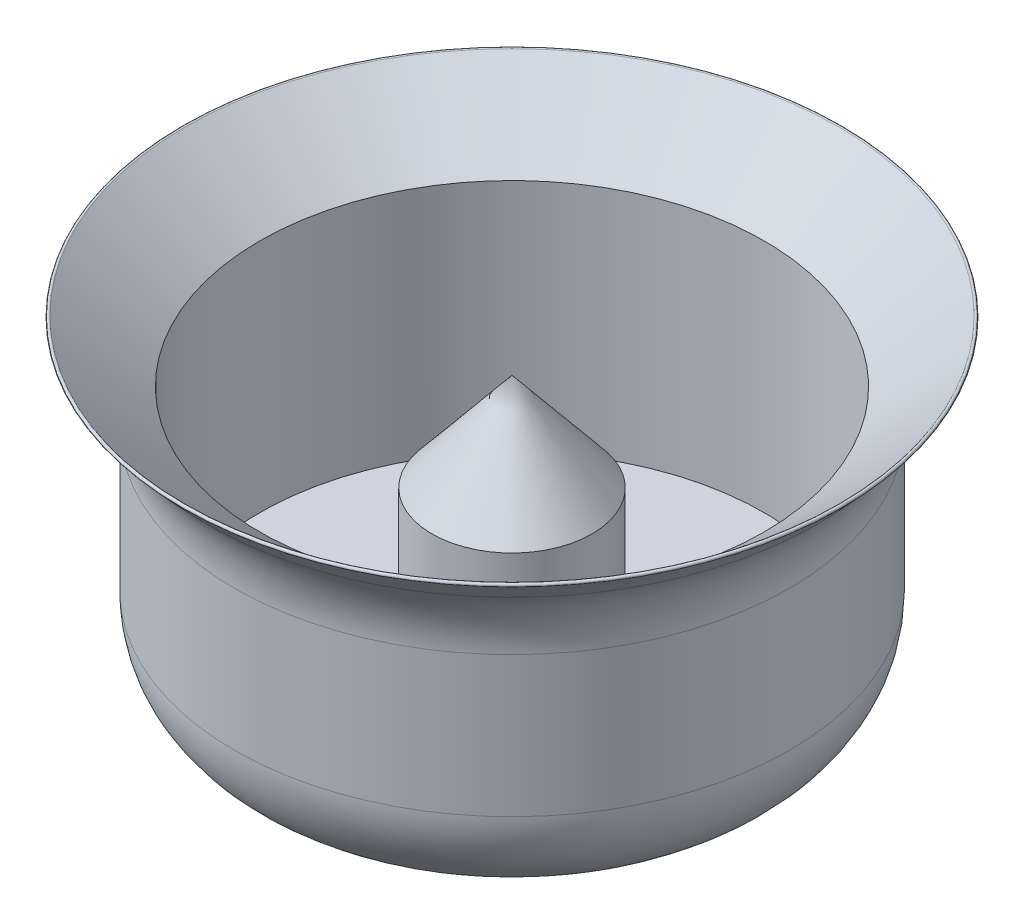
SolidWorks part; units mm, degrees
ref_plane "Front Plane" through (0, 0, 0) normal (0, 0, 1) x (1, 0, 0)
ref_plane "Top Plane" through (0, 0, 0) normal (0, 1, 0) x (1, 0, 0)
ref_plane "Right Plane" through (0, 0, 0) normal (1, 0, 0) x (0, 0, -1)
sketch "Sketch1" plane through (0, 0, 0) normal (0, 0, 1) x (1, 0, 0)
  line L0 (0, 0) -> (0, 17.0744)
  line L1 (4.765, 2.5) -> (4.765, 11.285)
  line L2 (4.765, 2.5) -> (15, 2.5)
  line L3 (0, 0) -> (25.2427, 0)
  line L4 (25.2427, 0) -> (16.5, 0)
  line L5 (15, 2.5) -> (15, 16.5)
  line L6 (20.6102, 21.1175) -> (16.5, 16.7128)
  line L7 (20.6102, 21.1175) -> (15, 16.5)
  line L8 (16.5, 16.7128) -> (16.5, 0)
  line L9 (0, 17.0744) -> (4.765, 11.285)
  dimension "D1" = 15
  dimension "D2" = 14
  dimension "D3" = 9.53
  dimension "D4" = 2.5
  dimension "D5" = 129.456
  dimension "D6" = 7.266
  dimension "D7" = 6.0245
  dimension "D8" = 8.785
  dimension "D9" = 1.5
revolve "Revolve1" add sketch "Sketch1" angle 360 about L0
fillet "Fillet1" radius 6 2 edges at (16.5, 0, 0) (16.5, 16.7128, 0)
fillet "Fillet2" radius 0.1 1 edges at (20.6102, 21.1175, 0)
